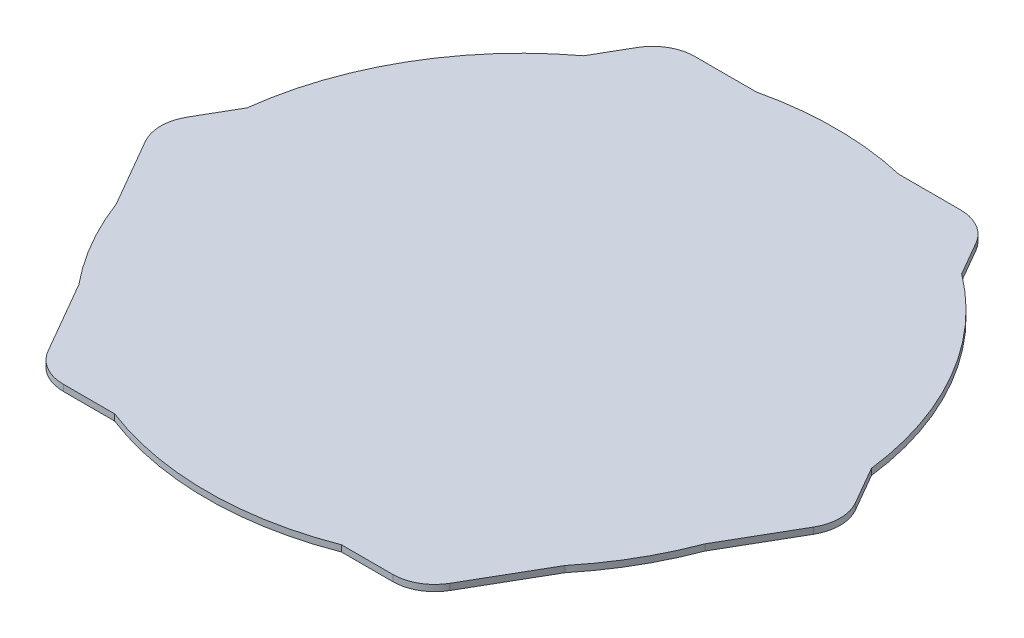
SolidWorks part; units mm, degrees
ref_plane "前基準面" through (0, 0, 0) normal (0, 0, 1) x (1, 0, 0)
ref_plane "上基準面" through (0, 0, 0) normal (0, 1, 0) x (1, 0, 0)
ref_plane "右基準面" through (0, 0, 0) normal (1, 0, 0) x (0, 0, -1)
sketch "草圖1" plane through (0, 0, 0) normal (0, 1, 0) x (1, 0, 0)
  line L0 (-90.1222, 0) -> (90.1222, 0)
  line L1 (90.1222, 0) -> (165.1222, 129.9038)
  line L2 (165.1222, 129.9038) -> (75, 286)
  line L3 (75, 286) -> (-75, 286)
  line L4 (-75, 286) -> (-165.1222, 129.9038)
  line L5 (-165.1222, 129.9038) -> (-90.1222, 0)
  dimension "D1" = 286
  dimension "D2" = 286
  dimension "D3" = 286
  dimension "D4" = 150
  dimension "D5" = 60
extrude "填料-伸長1" add sketch "草圖1" along normal blind 5
fillet "圓角1" radius 20 6 edges at (90.1222, 2.5, 0) (-90.1222, 2.5, 0) (-165.1222, 2.5, -129.9038) (-75, 2.5, -286) (75, 2.5, -286) (165.1222, 2.5, -129.9038)
sketch "草圖2" plane through (0, 5, 0) normal (0, 1, 0) x (1, 0, 0)
  line L0 (-127.6222, 64.9519) -> (120.0611, 207.9519) construction
  line L1 (-3.7805, 136.4519) -> (-127.2101, 350.2382) construction
  line L2 (-159.3487, 119.9038) -> (-95.8957, 10) construction
  line L3 (-11.7902, 180.325) -> (40.1714, 210.325)
  line L4 (40.1714, 210.325) -> (33.6714, 221.5833)
  line L5 (33.6714, 221.5833) -> (-18.2902, 191.5833)
  line L6 (-18.2902, 191.5833) -> (-11.7902, 180.325)
  line L7 (-44.2709, 176.5833) -> (-37.7709, 165.325)
  line L8 (-96.2324, 146.5833) -> (-44.2709, 176.5833)
  line L9 (-89.7324, 135.325) -> (-96.2324, 146.5833)
  line L10 (-37.7709, 165.325) -> (-89.7324, 135.325)
  line L11 (4.2291, 92.5788) -> (-47.7324, 62.5788)
  line L12 (-47.7324, 62.5788) -> (-41.2324, 51.3205)
  line L13 (-41.2324, 51.3205) -> (10.7291, 81.3205)
  line L14 (10.7291, 81.3205) -> (4.2291, 92.5788)
  line L15 (36.7098, 96.3205) -> (30.2098, 107.5788)
  line L16 (88.6714, 126.3205) -> (36.7098, 96.3205)
  line L17 (82.1714, 137.5788) -> (88.6714, 126.3205)
  line L18 (30.2098, 107.5788) -> (82.1714, 137.5788)
  line L19 (159.3487, 139.9038) -> (80.7735, 276) construction
  dimension "D1" = 13
  dimension "D2" = 150
  dimension "D3" = 110
  dimension "D4" = 60
extrude "除料-伸長1" [suppressed] cut sketch "草圖2" against normal blind 10
fillet "圓角2" [suppressed] radius 2
sketch "草圖3" plane through (0, 5, 0) normal (0, 1, 0) x (1, 0, 0)
  line L6 (-115.9652, 44.7614) -> (-95.8957, 10)
  line L8 (-148.9054, 157.9921) -> (-159.3487, 139.9038)
  line L9 (-33.9986, 286) -> (-63.453, 286)
  line L10 (90.1176, 259.8155) -> (80.7735, 276)
  line L11 (140.3783, 87.0462) -> (159.3487, 119.9038)
  line L12 (-78.5752, 0) -> (78.5752, 0)
  line L13 (95.8957, 10) -> (159.3487, 119.9038)
  line L14 (159.3487, 139.9038) -> (80.7735, 276)
  line L15 (63.453, 286) -> (-63.453, 286)
  line L16 (-80.7735, 276) -> (-159.3487, 139.9038)
  line L17 (-159.3487, 119.9038) -> (-95.8957, 10)
  line L18 (-78.5752, 0) -> (78.5752, 0)
  line L19 (95.8957, 10) -> (115.9652, 44.7614)
  line L20 (159.3487, 139.9038) -> (148.9054, 157.9921)
  line L21 (63.453, 286) -> (33.9986, 286)
  line L22 (-80.7735, 276) -> (-90.1176, 259.8155)
  line L23 (-159.3487, 119.9038) -> (-140.3783, 87.0462)
  arc A6 (-54.1011, 0) -> (54.1011, 0) centre (0, 139.9038) ccw
  arc A7 (-140.3783, 87.0462) -> (-115.9652, 44.7614) centre (0, 139.9038) ccw
  arc A8 (-90.1176, 259.8155) -> (-148.9054, 157.9921) centre (0, 139.9038) ccw
  arc A9 (33.9986, 286) -> (-33.9986, 286) centre (0, 139.9038) ccw
  arc A10 (148.9054, 157.9921) -> (90.1176, 259.8155) centre (0, 139.9038) ccw
  arc A11 (115.9652, 44.7614) -> (140.3783, 87.0462) centre (0, 139.9038) ccw
  arc A12 (78.5752, 0) -> (95.8957, 10) centre (78.5752, 20) ccw
  arc A13 (159.3487, 119.9038) -> (159.3487, 139.9038) centre (142.0282, 129.9038) ccw
  arc A14 (80.7735, 276) -> (63.453, 286) centre (63.453, 266) ccw
  arc A15 (-63.453, 286) -> (-80.7735, 276) centre (-63.453, 266) ccw
  arc A16 (-159.3487, 139.9038) -> (-159.3487, 119.9038) centre (-142.0282, 129.9038) ccw
  arc A17 (-95.8957, 10) -> (-78.5752, 0) centre (-78.5752, 20) ccw
  arc A18 (78.5752, 0) -> (95.8957, 10) centre (78.5752, 20) ccw
  arc A19 (159.3487, 119.9038) -> (159.3487, 139.9038) centre (142.0282, 129.9038) ccw
  arc A20 (80.7735, 276) -> (63.453, 286) centre (63.453, 266) ccw
  arc A21 (-63.453, 286) -> (-80.7735, 276) centre (-63.453, 266) ccw
  arc A22 (-159.3487, 139.9038) -> (-159.3487, 119.9038) centre (-142.0282, 129.9038) ccw
  arc A23 (-95.8957, 10) -> (-78.5752, 0) centre (-78.5752, 20) ccw
  dimension "D2" = 300
  dimension "D1" = 0
extrude "填料-伸長2" add sketch "草圖3" along normal blind 3
sketch "草圖5" plane through (0, 5, 0) normal (0, -1, 0) x (1, 0, 0)
  line L1 (-211.4881, -310.0556) -> (213.4108, -310.0556)
  line L2 (-211.4881, -310.0556) -> (-211.4881, 32.8115)
  line L3 (-211.4881, 32.8115) -> (213.4108, 32.8115)
  line L4 (213.4108, -310.0556) -> (213.4108, 32.8115)
extrude "除料-伸長2" cut sketch "草圖5" along normal blind 13
